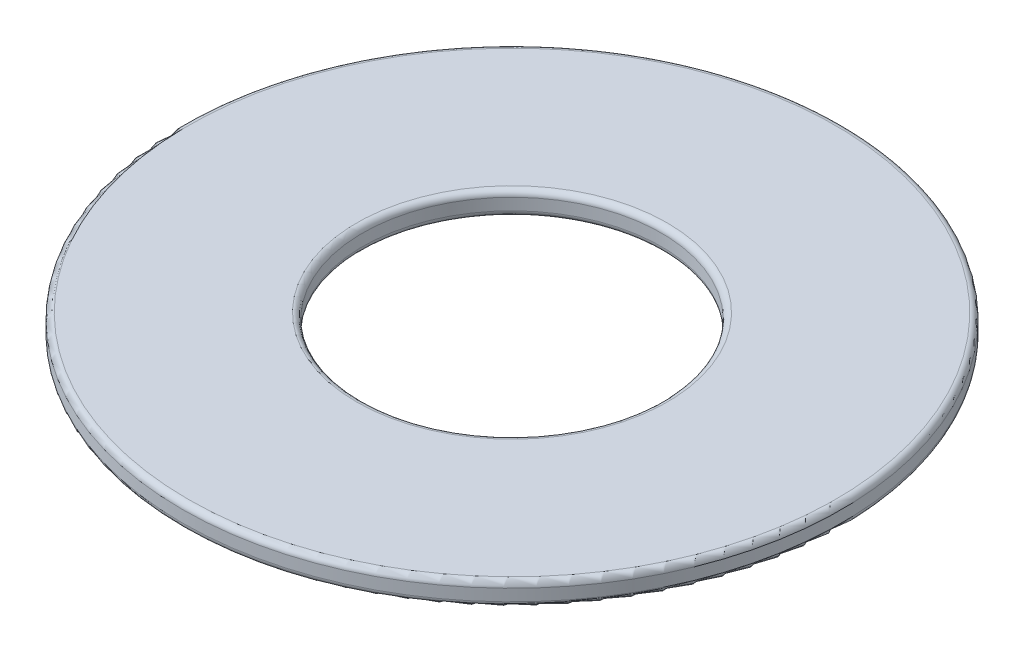
SolidWorks part; units mm, degrees
ref_plane "Front Plane" through (0, 0, 0) normal (0, 0, 1) x (1, 0, 0)
ref_plane "Top Plane" through (0, 0, 0) normal (0, 1, 0) x (1, 0, 0)
ref_plane "Right Plane" through (0, 0, 0) normal (1, 0, 0) x (0, 0, -1)
sketch "Sketch1" plane through (0, 0, 0) normal (0, 1, 0) x (1, 0, 0)
  circle A0 centre (0, 0) radius 3.2385
  circle A1 centre (0, 0) radius 7.1438
  dimension "D1" = 6.477
  dimension "D2" = 14.2875
extrude "Boss-Extrude1" add sketch "Sketch1" along normal blind 0.508
fillet "Fillet1" radius 0.127 4 edges at (0, 0.508, 3.2385) (0, 0, 3.2385) (0, 0, 7.1438) (0, 0.508, 7.1438)
